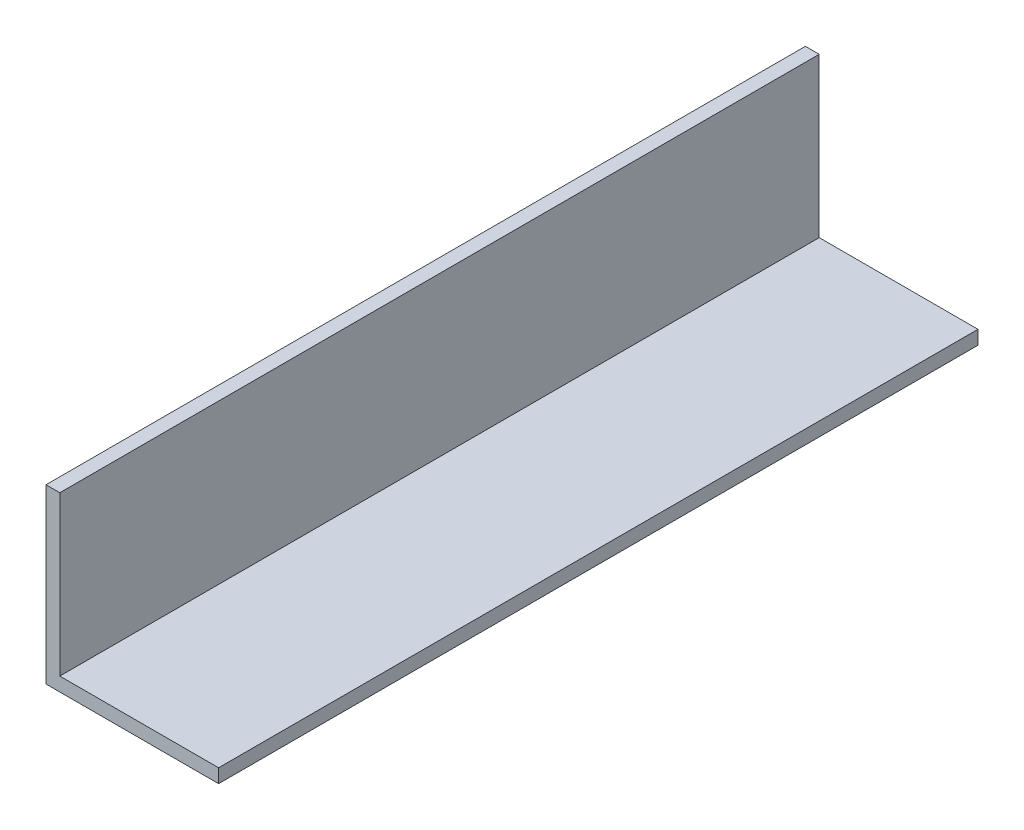
SolidWorks part; units mm, degrees
ref_plane "Front Plane" through (0, 0, 0) normal (0, 0, 1) x (1, 0, 0)
ref_plane "Top Plane" through (0, 0, 0) normal (0, 1, 0) x (1, 0, 0)
ref_plane "Right Plane" through (0, 0, 0) normal (1, 0, 0) x (0, 0, -1)
sketch "Sketch1" plane through (0, 0, 0) normal (0, 0, 1) x (1, 0, 0)
  line L0 (0, 0) -> (25, 0)
  line L1 (25, 0) -> (25, 2)
  line L2 (25, 2) -> (2, 2)
  line L3 (2, 2) -> (2, 25)
  line L4 (2, 25) -> (0, 25)
  line L5 (0, 25) -> (0, 0)
  dimension "D1" = 25
  dimension "D2" = 25
  dimension "D3" = 2
  dimension "D4" = 2
extrude "Boss-Extrude1" add sketch "Sketch1" along normal blind 110
